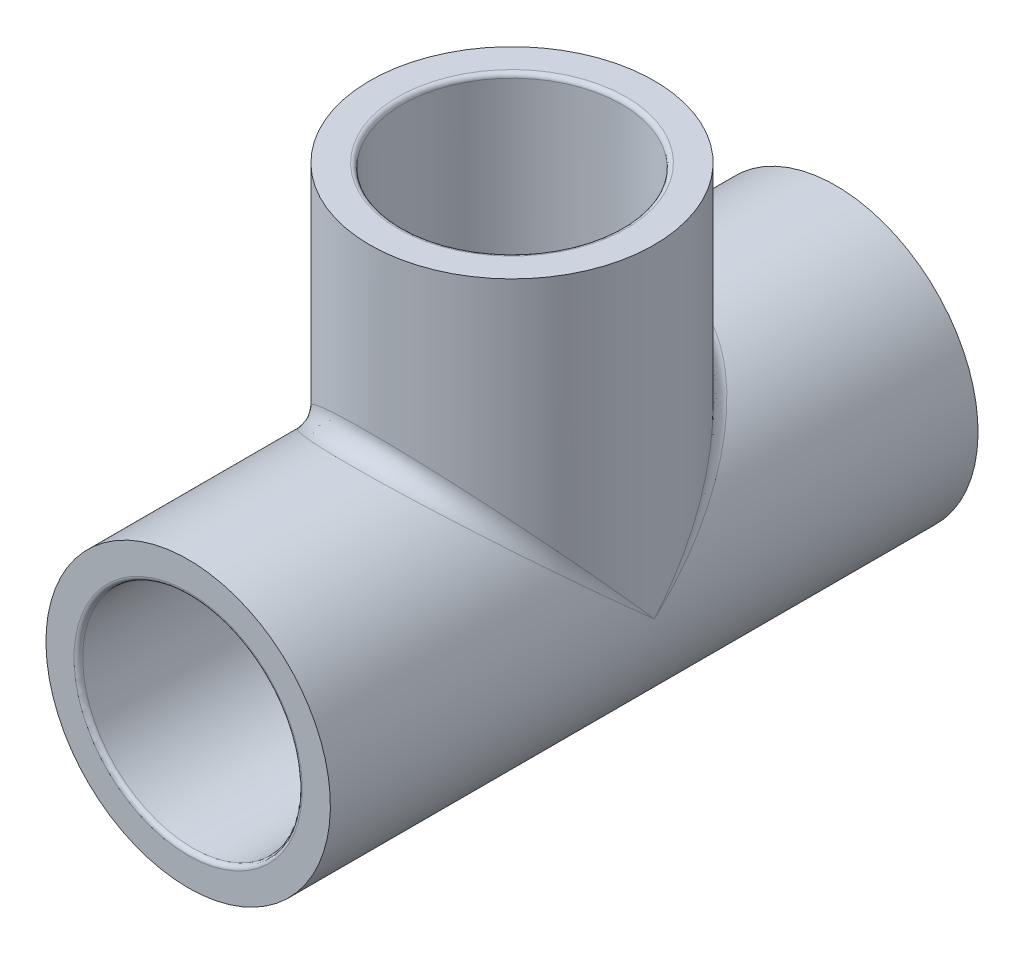
SolidWorks part; units mm, degrees
ref_plane "Front Plane" through (0, 0, 0) normal (0, 0, 1) x (1, 0, 0)
ref_plane "Top Plane" through (0, 0, 0) normal (0, 1, 0) x (1, 0, 0)
ref_plane "Right Plane" through (0, 0, 0) normal (1, 0, 0) x (0, 0, -1)
sketch "Sketch1" plane through (0, 0, 0) normal (1, 0, 0) x (0, 0, -1)
  line L0 (-31.75, 0) -> (31.75, 0) construction
  line L1 (-31.75, 0) -> (-31.75, -13.9446)
  line L2 (-31.75, -13.9446) -> (31.75, -13.9446)
  line L3 (31.75, -13.9446) -> (31.75, 0)
  line L4 (-31.75, -10.7696) -> (-12.7, -10.6172)
  line L5 (-12.7, -10.6172) -> (-12.7, -9.9568)
  line L6 (-12.7, -9.9568) -> (0, -9.9568)
  line L7 (0, -9.9568) -> (0, 0)
  line L8 (0, -9.9568) -> (0, -13.9446) construction
  point P2 (0, 0)
  dimension "Overall Length" = 63.5
  dimension "Diameter 1" = 21.5392
  dimension "Diameter 2" = 21.2344
  dimension "Wall 2" = 3.9878
  dimension "Wall 1" = 3.175
  dimension "Socket Depth" = 19.05
sketch "Sketch2" plane through (0, 0, 0) normal (1, 0, 0) x (0, 0, -1)
  line L0 (0, 0) -> (0, 31.75) construction
  line L1 (0, 31.75) -> (13.9446, 31.75)
  line L2 (13.9446, 31.75) -> (13.9446, 0)
  line L3 (-31.75, 0) -> (31.75, 0) construction
  line L4 (13.9446, 0) -> (0, 0)
  line L5 (10.7696, 31.75) -> (10.6172, 12.7)
  line L6 (10.6172, 12.7) -> (9.9695, 12.7)
  line L7 (9.9695, 12.7) -> (9.9695, 0)
  line L8 (-12.7, -9.9568) -> (0, -9.9568) construction
  dimension "Wall 3" = 3.175
  dimension "D1" = 21.5392
  dimension "D2" = 21.2344
  dimension "D3" = 19.05
  dimension "Diameter 3" = 19.939
sketch "Sketch3" plane through (0, 0, 0) normal (1, 0, 0) x (0, 0, -1)
  line L1 (-31.75, 0) -> (31.75, 0)
  line L2 (-31.75, 0) -> (-31.75, -13.9446)
  line L3 (-31.75, -13.9446) -> (31.75, -13.9446)
  line L4 (31.75, 0) -> (31.75, -13.9446)
revolve "Revolve1" add sketch "Sketch3" angle 360 about L1
sketch "Sketch4" plane through (0, 0, 0) normal (1, 0, 0) x (0, 0, -1)
  line L1 (0, 31.75) -> (13.9446, 31.75)
  line L2 (0, 31.75) -> (0, 0)
  line L3 (0, 0) -> (13.9446, 0)
  line L4 (13.9446, 31.75) -> (13.9446, 0)
revolve "Revolve2" add sketch "Sketch4" angle 360 about L2
sketch "Sketch5" plane through (0, 0, 0) normal (1, 0, 0) x (0, 0, -1)
  line L0 (-12.7, -9.9568) -> (0, -9.9568) construction
  line L1 (-12.7, -10.6172) -> (-12.7, -9.9568) construction
  line L2 (-31.75, -10.7696) -> (-12.7, -10.6172) construction
  line L3 (-12.7, -9.9568) -> (12.7, -9.9568)
  line L4 (-12.7, -10.6172) -> (-12.7, -9.9568)
  line L5 (-31.75, -10.7696) -> (-12.7, -10.6172)
  line L6 (-31.75, -10.7696) -> (-31.75, 0)
  line L7 (-31.75, 0) -> (31.75, 0)
  line L8 (0, 0) -> (0, -9.9568) construction
  line L9 (12.7, -10.6172) -> (12.7, -9.9568)
  line L10 (31.75, -10.7696) -> (12.7, -10.6172)
  line L11 (31.75, -10.7696) -> (31.75, 0)
revolve "Cut-Revolve1" cut sketch "Sketch5" angle 360 about L7
sketch "Sketch6" plane through (0, 0, 0) normal (1, 0, 0) x (0, 0, -1)
  line L0 (9.9695, 0) -> (9.9695, 12.7)
  line L1 (9.9695, 12.7) -> (10.6172, 12.7)
  line L2 (10.7696, 31.75) -> (10.6172, 12.7) construction
  line L3 (10.7696, 31.75) -> (10.6172, 12.7)
  line L4 (0, 0) -> (0, 31.75) construction
  line L5 (0, 0) -> (0, 31.75)
  line L6 (0, 31.75) -> (10.7696, 31.75)
  line L7 (0, 0) -> (9.9695, 0)
revolve "Cut-Revolve2" cut sketch "Sketch6" angle 360 about L5
fillet "Fillet1" radius 0.1619 3 edges at (0, -10.6172, -12.7) (0, 12.7, -10.6172) (0, -10.6172, 12.7)
fillet "Fillet2" radius 0.4308 3 edges at (0, -10.7696, -31.75) (0, 31.75, -10.7696) (0, -10.7696, 31.75)
fillet "Fillet3" radius 1.8536 2 edges at (0, 13.9446, 13.9446) (0, 13.9446, -13.9446)
sketch "Sketch7" plane through (0, 0, 0) normal (1, 0, 0) x (0, 0, -1)
  line L0 (-12.7, -9.9568) -> (0, -9.9568) construction
  line L1 (-12.7, -10.6172) -> (-12.7, -9.9568) construction
  line L2 (-31.75, -10.7696) -> (-12.7, -10.6172) construction
  line L3 (-12.7, -9.9568) -> (12.7, -9.9568)
  line L4 (-12.7, -10.6172) -> (-12.7, -9.9568)
  line L5 (-31.75, -10.7696) -> (-12.7, -10.6172)
  line L6 (0, 0) -> (0, -9.9568) construction
  line L7 (0, 0) -> (-31.75, 0) construction
  line L8 (-12.7, 9.9568) -> (-9.9695, 9.9568)
  line L9 (-12.7, 10.6172) -> (-12.7, 9.9568)
  line L10 (-31.75, 10.7696) -> (-12.7, 10.6172)
  line L11 (10.7696, 31.75) -> (10.6172, 12.7) construction
  line L12 (10.6172, 12.7) -> (9.9695, 12.7) construction
  line L13 (9.9695, 12.7) -> (9.9695, 0) construction
  line L14 (10.7696, 31.75) -> (10.6172, 12.7)
  line L15 (10.6172, 12.7) -> (9.9695, 12.7)
  line L16 (9.9695, 12.7) -> (9.9695, 9.9568)
  line L17 (-9.9695, 12.7) -> (-9.9695, 9.9568)
  line L18 (-10.6172, 12.7) -> (-9.9695, 12.7)
  line L19 (-10.7696, 31.75) -> (-10.6172, 12.7)
  line L20 (12.7, -10.6172) -> (12.7, -9.9568)
  line L21 (31.75, -10.7696) -> (12.7, -10.6172)
  line L22 (12.7, 10.6172) -> (12.7, 9.9568)
  line L23 (31.75, 10.7696) -> (12.7, 10.6172)
  line L24 (9.9695, 9.9568) -> (12.7, 9.9568)
  point P24 (0, 9.9568)
  point P29 (-31.75, -10.7696)
equation "\"D1@Sketch2\"=\"Diameter 1@Sketch1\""
equation "\"D2@Sketch2\"=\"Diameter 2@Sketch1\""
equation "\"D3@Sketch2\"=\"Socket Depth@Sketch1\""
equation "\"D1@Fillet1\"=0.25*(\"Diameter 2@Sketch1\"-\"Diameter 3@Sketch2\")*0.5"
equation "\"D1@Fillet2\"=.02*\"Diameter 1@Sketch1\""
equation "\"D1@Fillet3\"=.075*(\"Diameter 1@Sketch1\"+\"Wall 1@Sketch1\")"
